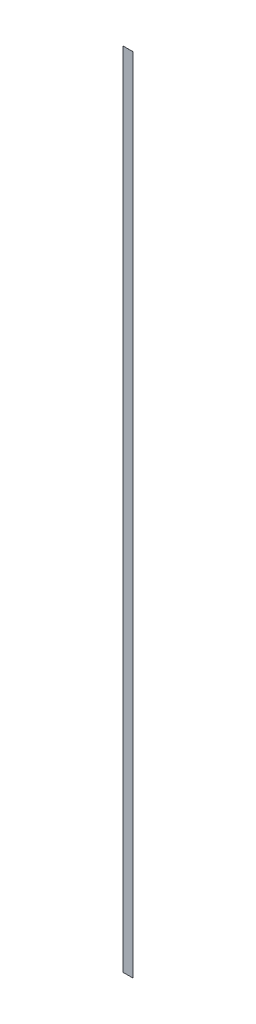
SolidWorks part; units mm, degrees
material "Ferro duttile"
ref_plane "Piano frontale" through (0, 0, 0) normal (0, 0, 1) x (1, 0, 0)
ref_plane "Piano superiore" through (0, 0, 0) normal (0, 1, 0) x (1, 0, 0)
ref_plane "Piano destro" through (0, 0, 0) normal (1, 0, 0) x (0, 0, -1)
sketch "Schizzo1" plane through (0, 0, 0) normal (0, 0, 1) x (1, 0, 0)
  line L1 (0, 0) -> (-3000, 0)
  line L2 (0, 0) -> (0, 250000)
  line L3 (0, 250000) -> (-3000, 250000)
  line L4 (-3000, 0) -> (-3000, 250000)
  dimension "D1" = 3000
  dimension "D2" = 250000
extrude "Estrusione-Estrusione1" add sketch "Schizzo1" along normal blind 15
